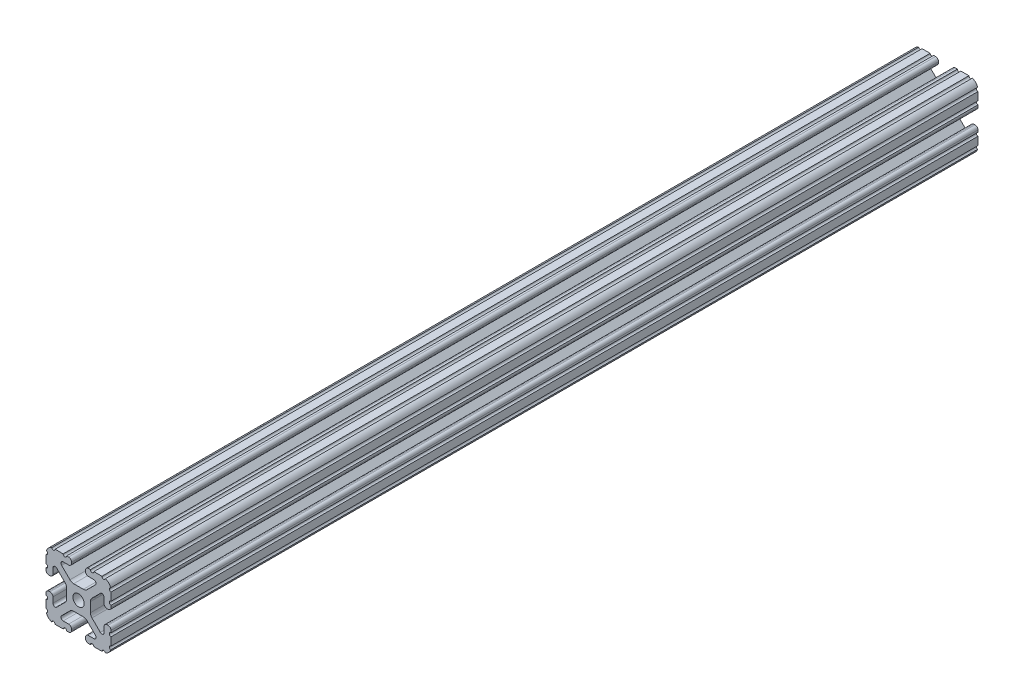
SolidWorks part; units mm, degrees
ref_plane "Front Plane" through (0, 0, 0) normal (0, 0, 1) x (1, 0, 0)
ref_plane "Top Plane" through (0, 0, 0) normal (0, 1, 0) x (1, 0, 0)
ref_plane "Right Plane" through (0, 0, 0) normal (1, 0, 0) x (0, 0, -1)
sketch "Sketch2" plane through (0, 0, 0) normal (0, 0, 1) x (1, 0, 0)
  line L0 (0, 19.05) -> (0, -19.05) construction
  line L1 (-19.05, 0) -> (19.05, 0) construction
  line L2 (4.064, -19.05) -> (19.05, -19.05)
  line L3 (19.05, -19.05) -> (19.05, -4.064)
  line L4 (4.064, -19.05) -> (4.064, -14.986)
  line L5 (4.064, -14.986) -> (12.1123, -14.986)
  line L6 (12.1123, -14.986) -> (4.1113, -6.985)
  line L7 (0, 0) -> (19.05, -19.05) construction
  line L8 (19.05, -4.064) -> (14.986, -4.064)
  line L9 (14.986, -4.064) -> (14.986, -12.1123)
  line L10 (14.986, -12.1123) -> (6.985, -4.1113)
  circle A0 centre (0, 0) radius 3.3274
  arc A1 (8.9963, -14.986) -> (9.909, -12.7826) centre (8.9963, -13.6953) ccw construction
  point P8 (0, -6.985)
  dimension "Center Hole Diameter" = 6.6548
  dimension "Rail Height" = 38.1
  dimension "Rail Width" = 38.1
  dimension "T-Slot Width" = 8.128
  dimension "Slot Inner Width" = 20.574
  dimension "Thickness" = 4.064
  dimension "Slot Depth" = 8.001
  dimension "D1" = 4.064
sketch "Sketch3" plane through (0, 0, 0) normal (1, 0, 0) x (0, 0, -1)
  line L0 (-304.8, -19.05) -> (304.8, -19.05) construction
  line L1 (-279.4, 0) -> (279.4, 0) construction
  dimension "Length" = 609.6
  dimension "D1" = 25.4
sketch "Sketch4" plane through (0, 0, 0) normal (0, 0, 1) x (1, 0, 0)
  line L0 (5.7912, -19.05) -> (14.3002, -19.05)
  line L1 (4.064, -19.05) -> (19.05, -19.05) construction
  line L2 (4.064, -19.05) -> (4.064, -14.986) construction
  line L3 (4.064, -14.986) -> (12.1123, -14.986) construction
  line L4 (4.064, -16.7132) -> (4.064, -17.3228)
  line L5 (5.7912, -14.986) -> (8.9963, -14.986)
  line L6 (0, -6.985) -> (2.833, -6.985)
  line L7 (12.1123, -14.986) -> (4.1113, -6.985) construction
  line L8 (5.0152, -7.8889) -> (9.909, -12.7826)
  line L9 (19.05, -19.05) -> (19.05, -4.064) construction
  line L10 (14.986, -12.1123) -> (6.985, -4.1113) construction
  line L11 (14.986, -4.064) -> (14.986, -12.1123) construction
  line L12 (14.986, -8.9963) -> (14.986, -5.7912)
  line L13 (19.05, -4.064) -> (14.986, -4.064) construction
  line L14 (16.7132, -4.064) -> (17.3228, -4.064)
  line L15 (19.05, -5.7912) -> (19.05, -14.3002)
  line L16 (12.7826, -9.909) -> (7.8889, -5.0152)
  line L17 (6.985, 0) -> (6.985, -2.833)
  line L18 (-19.05, 0) -> (19.05, 0) construction
  line L19 (0, -6.985) -> (0, -3.3274)
  line L20 (0, 19.05) -> (0, -19.05) construction
  line L21 (6.985, 0) -> (3.3274, 0)
  arc A0 (4.064, -17.3228) -> (5.7912, -19.05) centre (5.7912, -17.3228) ccw
  arc A2 (4.064, -16.7132) -> (5.7912, -14.986) centre (5.7912, -16.7132) cw
  arc A3 (8.9963, -14.986) -> (9.909, -12.7826) centre (8.9963, -13.6953) ccw
  arc A4 (2.833, -6.985) -> (5.0152, -7.8889) centre (2.833, -10.0711) cw
  arc A5 (14.3002, -19.05) -> (19.05, -14.3002) centre (14.3002, -14.3002) ccw
  arc A6 (12.7826, -9.909) -> (14.986, -8.9963) centre (13.6953, -8.9963) ccw
  arc A7 (14.986, -5.7912) -> (16.7132, -4.064) centre (16.7132, -5.7912) cw
  arc A8 (17.3228, -4.064) -> (19.05, -5.7912) centre (17.3228, -5.7912) cw
  arc A9 (7.8889, -5.0152) -> (6.985, -2.833) centre (10.0711, -2.833) cw
  circle A10 centre (0, 0) radius 3.3274 construction
  arc A11 (0, -3.3274) -> (3.3274, 0) centre (0, 0) ccw
  dimension "D1" = 4.7498
  dimension "D2" = 3.0861
  dimension "D3" = 1.7272
extrude "Boss-Extrude1" add sketch "Sketch4" along normal mid plane 609.6
sketch "Sketch5" plane through (0, 0, 0) normal (0, 0, 1) x (1, 0, 0)
  line L0 (4.064, -19.05) -> (19.05, -19.05) construction
  line L1 (5.7912, -14.986) -> (8.9963, -14.986) construction
  line L3 (0, 0) -> (19.05, -19.05) construction
  line L4 (8.9963, -14.986) -> (8.9963, -19.05) construction
  line L5 (12.1123, -14.986) -> (4.1113, -6.985) construction
  circle A0 centre (14.7395, -19.05) radius 1.016
  circle A1 centre (7.9803, -19.05) radius 1.016
  circle A2 centre (19.05, -14.7395) radius 1.016
  circle A3 centre (19.05, -7.9803) radius 1.016
  point P10 (7.3938, -14.986)
  point P12 (13.6953, -8.9963)
extrude "Cut-Extrude1" cut sketch "Sketch5" against normal through all both and the other way through all
mirror "Mirror1" about plane through (0, 0, 0) normal (1, 0, 0) of bodies 137 134
mirror "Mirror2" about plane through (0, 0, 0) normal (0, 1, 0) of bodies 135
sketch "Sketch6" plane through (0, 0, -304.8) normal (0, 0, -1) x (-1, 0, 0)
  line L44 (-19.05, -5.7912) -> (-19.05, -6.9643)
  line L45 (-19.05, -8.9963) -> (-19.05, -13.7235)
  line L46 (-13.7235, -19.05) -> (-8.9963, -19.05)
  line L47 (-6.9643, -19.05) -> (-5.7912, -19.05)
  line L48 (-4.064, -17.3228) -> (-4.064, -16.7132)
  line L49 (-5.7912, -14.986) -> (-8.9963, -14.986)
  line L50 (-9.909, -12.7826) -> (-5.0152, -7.8889)
  line L51 (-2.833, -6.985) -> (2.833, -6.985)
  line L52 (5.0152, -7.8889) -> (9.909, -12.7826)
  line L53 (8.9963, -14.986) -> (5.7912, -14.986)
  line L54 (4.064, -16.7132) -> (4.064, -17.3228)
  line L55 (5.7912, -19.05) -> (6.9643, -19.05)
  line L56 (8.9963, -19.05) -> (13.7235, -19.05)
  line L57 (19.05, -13.7235) -> (19.05, -8.9963)
  line L58 (19.05, -6.9643) -> (19.05, -5.7912)
  line L59 (17.3228, -4.064) -> (16.7132, -4.064)
  line L60 (14.986, -5.7912) -> (14.986, -8.9963)
  line L61 (12.7826, -9.909) -> (7.8889, -5.0152)
  line L62 (6.985, -2.833) -> (6.985, 2.833)
  line L63 (7.8889, 5.0152) -> (12.7826, 9.909)
  line L64 (14.986, 8.9963) -> (14.986, 5.7912)
  line L65 (16.7132, 4.064) -> (17.3228, 4.064)
  line L66 (19.05, 5.7912) -> (19.05, 6.9643)
  line L67 (19.05, 8.9963) -> (19.05, 13.7235)
  line L68 (13.7235, 19.05) -> (8.9963, 19.05)
  line L69 (6.9643, 19.05) -> (5.7912, 19.05)
  line L70 (4.064, 17.3228) -> (4.064, 16.7132)
  line L71 (5.7912, 14.986) -> (8.9963, 14.986)
  line L72 (9.909, 12.7826) -> (5.0152, 7.8889)
  line L73 (2.833, 6.985) -> (-2.833, 6.985)
  line L74 (-5.0152, 7.8889) -> (-9.909, 12.7826)
  line L75 (-8.9963, 14.986) -> (-5.7912, 14.986)
  line L76 (-4.064, 16.7132) -> (-4.064, 17.3228)
  line L77 (-5.7912, 19.05) -> (-6.9643, 19.05)
  line L78 (-8.9963, 19.05) -> (-13.7235, 19.05)
  line L79 (-19.05, 13.7235) -> (-19.05, 8.9963)
  line L80 (-19.05, 6.9643) -> (-19.05, 5.7912)
  line L81 (-17.3228, 4.064) -> (-16.7132, 4.064)
  line L82 (-14.986, 5.7912) -> (-14.986, 8.9963)
  line L83 (-12.7826, 9.909) -> (-7.8889, 5.0152)
  line L84 (-6.985, 2.833) -> (-6.985, -2.833)
  line L85 (-7.8889, -5.0152) -> (-12.7826, -9.909)
  line L86 (-14.986, -8.9963) -> (-14.986, -5.7912)
  line L87 (-16.7132, -4.064) -> (-17.3228, -4.064)
  line L88 (-19.05, -5.7912) -> (-19.05, -6.9643)
  line L89 (-19.05, -8.9963) -> (-19.05, -13.7235)
  line L90 (-13.7235, -19.05) -> (-8.9963, -19.05)
  line L91 (-6.9643, -19.05) -> (-5.7912, -19.05)
  line L92 (-4.064, -17.3228) -> (-4.064, -16.7132)
  line L93 (-5.7912, -14.986) -> (-8.9963, -14.986)
  line L94 (-9.909, -12.7826) -> (-5.0152, -7.8889)
  line L95 (-2.833, -6.985) -> (2.833, -6.985)
  line L96 (5.0152, -7.8889) -> (9.909, -12.7826)
  line L97 (8.9963, -14.986) -> (5.7912, -14.986)
  line L98 (4.064, -16.7132) -> (4.064, -17.3228)
  line L99 (5.7912, -19.05) -> (6.9643, -19.05)
  line L100 (8.9963, -19.05) -> (13.7235, -19.05)
  line L101 (19.05, -13.7235) -> (19.05, -8.9963)
  line L102 (19.05, -6.9643) -> (19.05, -5.7912)
  line L103 (17.3228, -4.064) -> (16.7132, -4.064)
  line L104 (14.986, -5.7912) -> (14.986, -8.9963)
  line L105 (12.7826, -9.909) -> (7.8889, -5.0152)
  line L106 (6.985, -2.833) -> (6.985, 2.833)
  line L107 (7.8889, 5.0152) -> (12.7826, 9.909)
  line L108 (14.986, 8.9963) -> (14.986, 5.7912)
  line L109 (16.7132, 4.064) -> (17.3228, 4.064)
  line L110 (19.05, 5.7912) -> (19.05, 6.9643)
  line L111 (19.05, 8.9963) -> (19.05, 13.7235)
  line L112 (13.7235, 19.05) -> (8.9963, 19.05)
  line L113 (6.9643, 19.05) -> (5.7912, 19.05)
  line L114 (4.064, 17.3228) -> (4.064, 16.7132)
  line L115 (5.7912, 14.986) -> (8.9963, 14.986)
  line L116 (9.909, 12.7826) -> (5.0152, 7.8889)
  line L117 (2.833, 6.985) -> (-2.833, 6.985)
  line L118 (-5.0152, 7.8889) -> (-9.909, 12.7826)
  line L119 (-8.9963, 14.986) -> (-5.7912, 14.986)
  line L120 (-4.064, 16.7132) -> (-4.064, 17.3228)
  line L121 (-5.7912, 19.05) -> (-6.9643, 19.05)
  line L122 (-8.9963, 19.05) -> (-13.7235, 19.05)
  line L123 (-19.05, 13.7235) -> (-19.05, 8.9963)
  line L124 (-19.05, 6.9643) -> (-19.05, 5.7912)
  line L125 (-17.3228, 4.064) -> (-16.7132, 4.064)
  line L126 (-14.986, 5.7912) -> (-14.986, 8.9963)
  line L127 (-12.7826, 9.909) -> (-7.8889, 5.0152)
  line L128 (-6.985, 2.833) -> (-6.985, -2.833)
  line L129 (-7.8889, -5.0152) -> (-12.7826, -9.909)
  line L130 (-14.986, -8.9963) -> (-14.986, -5.7912)
  line L131 (-16.7132, -4.064) -> (-17.3228, -4.064)
  circle A1 centre (0, 0) radius 3.3274
  circle A2 centre (0, 0) radius 3.3274
  arc A54 (-19.05, -8.9963) -> (-19.05, -6.9643) centre (-19.05, -7.9803) ccw
  arc A55 (-18.8293, -15.7312) -> (-19.05, -13.7235) centre (-19.05, -14.7395) ccw
  arc A56 (-18.8293, -15.7312) -> (-15.7312, -18.8293) centre (-14.3002, -14.3002) ccw
  arc A57 (-13.7235, -19.05) -> (-15.7312, -18.8293) centre (-14.7395, -19.05) ccw
  arc A58 (-6.9643, -19.05) -> (-8.9963, -19.05) centre (-7.9803, -19.05) ccw
  arc A59 (-5.7912, -19.05) -> (-4.064, -17.3228) centre (-5.7912, -17.3228) ccw
  arc A60 (-4.064, -16.7132) -> (-5.7912, -14.986) centre (-5.7912, -16.7132) ccw
  arc A61 (-9.909, -12.7826) -> (-8.9963, -14.986) centre (-8.9963, -13.6953) ccw
  arc A62 (-2.833, -6.985) -> (-5.0152, -7.8889) centre (-2.833, -10.0711) ccw
  arc A63 (5.0152, -7.8889) -> (2.833, -6.985) centre (2.833, -10.0711) ccw
  arc A64 (8.9963, -14.986) -> (9.909, -12.7826) centre (8.9963, -13.6953) ccw
  arc A65 (5.7912, -14.986) -> (4.064, -16.7132) centre (5.7912, -16.7132) ccw
  arc A66 (4.064, -17.3228) -> (5.7912, -19.05) centre (5.7912, -17.3228) ccw
  arc A67 (8.9963, -19.05) -> (6.9643, -19.05) centre (7.9803, -19.05) ccw
  arc A68 (15.7312, -18.8293) -> (13.7235, -19.05) centre (14.7395, -19.05) ccw
  arc A69 (15.7312, -18.8293) -> (18.8293, -15.7312) centre (14.3002, -14.3002) ccw
  arc A70 (19.05, -13.7235) -> (18.8293, -15.7312) centre (19.05, -14.7395) ccw
  arc A71 (19.05, -6.9643) -> (19.05, -8.9963) centre (19.05, -7.9803) ccw
  arc A72 (19.05, -5.7912) -> (17.3228, -4.064) centre (17.3228, -5.7912) ccw
  arc A73 (16.7132, -4.064) -> (14.986, -5.7912) centre (16.7132, -5.7912) ccw
  arc A74 (12.7826, -9.909) -> (14.986, -8.9963) centre (13.6953, -8.9963) ccw
  arc A75 (6.985, -2.833) -> (7.8889, -5.0152) centre (10.0711, -2.833) ccw
  arc A76 (7.8889, 5.0152) -> (6.985, 2.833) centre (10.0711, 2.833) ccw
  arc A77 (14.986, 8.9963) -> (12.7826, 9.909) centre (13.6953, 8.9963) ccw
  arc A78 (14.986, 5.7912) -> (16.7132, 4.064) centre (16.7132, 5.7912) ccw
  arc A79 (17.3228, 4.064) -> (19.05, 5.7912) centre (17.3228, 5.7912) ccw
  arc A80 (19.05, 8.9963) -> (19.05, 6.9643) centre (19.05, 7.9803) ccw
  arc A81 (18.8293, 15.7312) -> (19.05, 13.7235) centre (19.05, 14.7395) ccw
  arc A82 (18.8293, 15.7312) -> (15.7312, 18.8293) centre (14.3002, 14.3002) ccw
  arc A83 (13.7235, 19.05) -> (15.7312, 18.8293) centre (14.7395, 19.05) ccw
  arc A84 (6.9643, 19.05) -> (8.9963, 19.05) centre (7.9803, 19.05) ccw
  arc A85 (5.7912, 19.05) -> (4.064, 17.3228) centre (5.7912, 17.3228) ccw
  arc A86 (4.064, 16.7132) -> (5.7912, 14.986) centre (5.7912, 16.7132) ccw
  arc A87 (9.909, 12.7826) -> (8.9963, 14.986) centre (8.9963, 13.6953) ccw
  arc A88 (2.833, 6.985) -> (5.0152, 7.8889) centre (2.833, 10.0711) ccw
  arc A89 (-5.0152, 7.8889) -> (-2.833, 6.985) centre (-2.833, 10.0711) ccw
  arc A90 (-8.9963, 14.986) -> (-9.909, 12.7826) centre (-8.9963, 13.6953) ccw
  arc A91 (-5.7912, 14.986) -> (-4.064, 16.7132) centre (-5.7912, 16.7132) ccw
  arc A92 (-4.064, 17.3228) -> (-5.7912, 19.05) centre (-5.7912, 17.3228) ccw
  arc A93 (-8.9963, 19.05) -> (-6.9643, 19.05) centre (-7.9803, 19.05) ccw
  arc A94 (-15.7312, 18.8293) -> (-13.7235, 19.05) centre (-14.7395, 19.05) ccw
  arc A95 (-15.7312, 18.8293) -> (-18.8293, 15.7312) centre (-14.3002, 14.3002) ccw
  arc A96 (-19.05, 13.7235) -> (-18.8293, 15.7312) centre (-19.05, 14.7395) ccw
  arc A97 (-19.05, 6.9643) -> (-19.05, 8.9963) centre (-19.05, 7.9803) ccw
  arc A98 (-19.05, 5.7912) -> (-17.3228, 4.064) centre (-17.3228, 5.7912) ccw
  arc A99 (-16.7132, 4.064) -> (-14.986, 5.7912) centre (-16.7132, 5.7912) ccw
  arc A100 (-12.7826, 9.909) -> (-14.986, 8.9963) centre (-13.6953, 8.9963) ccw
  arc A101 (-6.985, 2.833) -> (-7.8889, 5.0152) centre (-10.0711, 2.833) ccw
  arc A102 (-7.8889, -5.0152) -> (-6.985, -2.833) centre (-10.0711, -2.833) ccw
  arc A103 (-14.986, -8.9963) -> (-12.7826, -9.909) centre (-13.6953, -8.9963) ccw
  arc A104 (-14.986, -5.7912) -> (-16.7132, -4.064) centre (-16.7132, -5.7912) ccw
  arc A105 (-17.3228, -4.064) -> (-19.05, -5.7912) centre (-17.3228, -5.7912) ccw
  arc A106 (-19.05, -8.9963) -> (-19.05, -6.9643) centre (-19.05, -7.9803) ccw
  arc A107 (-18.8293, -15.7312) -> (-19.05, -13.7235) centre (-19.05, -14.7395) ccw
  arc A108 (-18.8293, -15.7312) -> (-15.7312, -18.8293) centre (-14.3002, -14.3002) ccw
  arc A109 (-13.7235, -19.05) -> (-15.7312, -18.8293) centre (-14.7395, -19.05) ccw
  arc A110 (-6.9643, -19.05) -> (-8.9963, -19.05) centre (-7.9803, -19.05) ccw
  arc A111 (-5.7912, -19.05) -> (-4.064, -17.3228) centre (-5.7912, -17.3228) ccw
  arc A112 (-4.064, -16.7132) -> (-5.7912, -14.986) centre (-5.7912, -16.7132) ccw
  arc A113 (-9.909, -12.7826) -> (-8.9963, -14.986) centre (-8.9963, -13.6953) ccw
  arc A114 (-2.833, -6.985) -> (-5.0152, -7.8889) centre (-2.833, -10.0711) ccw
  arc A115 (5.0152, -7.8889) -> (2.833, -6.985) centre (2.833, -10.0711) ccw
  arc A116 (8.9963, -14.986) -> (9.909, -12.7826) centre (8.9963, -13.6953) ccw
  arc A117 (5.7912, -14.986) -> (4.064, -16.7132) centre (5.7912, -16.7132) ccw
  arc A118 (4.064, -17.3228) -> (5.7912, -19.05) centre (5.7912, -17.3228) ccw
  arc A119 (8.9963, -19.05) -> (6.9643, -19.05) centre (7.9803, -19.05) ccw
  arc A120 (15.7312, -18.8293) -> (13.7235, -19.05) centre (14.7395, -19.05) ccw
  arc A121 (15.7312, -18.8293) -> (18.8293, -15.7312) centre (14.3002, -14.3002) ccw
  arc A122 (19.05, -13.7235) -> (18.8293, -15.7312) centre (19.05, -14.7395) ccw
  arc A123 (19.05, -6.9643) -> (19.05, -8.9963) centre (19.05, -7.9803) ccw
  arc A124 (19.05, -5.7912) -> (17.3228, -4.064) centre (17.3228, -5.7912) ccw
  arc A125 (16.7132, -4.064) -> (14.986, -5.7912) centre (16.7132, -5.7912) ccw
  arc A126 (12.7826, -9.909) -> (14.986, -8.9963) centre (13.6953, -8.9963) ccw
  arc A127 (6.985, -2.833) -> (7.8889, -5.0152) centre (10.0711, -2.833) ccw
  arc A128 (7.8889, 5.0152) -> (6.985, 2.833) centre (10.0711, 2.833) ccw
  arc A129 (14.986, 8.9963) -> (12.7826, 9.909) centre (13.6953, 8.9963) ccw
  arc A130 (14.986, 5.7912) -> (16.7132, 4.064) centre (16.7132, 5.7912) ccw
  arc A131 (17.3228, 4.064) -> (19.05, 5.7912) centre (17.3228, 5.7912) ccw
  arc A132 (19.05, 8.9963) -> (19.05, 6.9643) centre (19.05, 7.9803) ccw
  arc A133 (18.8293, 15.7312) -> (19.05, 13.7235) centre (19.05, 14.7395) ccw
  arc A134 (18.8293, 15.7312) -> (15.7312, 18.8293) centre (14.3002, 14.3002) ccw
  arc A135 (13.7235, 19.05) -> (15.7312, 18.8293) centre (14.7395, 19.05) ccw
  arc A136 (6.9643, 19.05) -> (8.9963, 19.05) centre (7.9803, 19.05) ccw
  arc A137 (5.7912, 19.05) -> (4.064, 17.3228) centre (5.7912, 17.3228) ccw
  arc A138 (4.064, 16.7132) -> (5.7912, 14.986) centre (5.7912, 16.7132) ccw
  arc A139 (9.909, 12.7826) -> (8.9963, 14.986) centre (8.9963, 13.6953) ccw
  arc A140 (2.833, 6.985) -> (5.0152, 7.8889) centre (2.833, 10.0711) ccw
  arc A141 (-5.0152, 7.8889) -> (-2.833, 6.985) centre (-2.833, 10.0711) ccw
  arc A142 (-8.9963, 14.986) -> (-9.909, 12.7826) centre (-8.9963, 13.6953) ccw
  arc A143 (-5.7912, 14.986) -> (-4.064, 16.7132) centre (-5.7912, 16.7132) ccw
  arc A144 (-4.064, 17.3228) -> (-5.7912, 19.05) centre (-5.7912, 17.3228) ccw
  arc A145 (-8.9963, 19.05) -> (-6.9643, 19.05) centre (-7.9803, 19.05) ccw
  arc A146 (-15.7312, 18.8293) -> (-13.7235, 19.05) centre (-14.7395, 19.05) ccw
  arc A147 (-15.7312, 18.8293) -> (-18.8293, 15.7312) centre (-14.3002, 14.3002) ccw
  arc A148 (-19.05, 13.7235) -> (-18.8293, 15.7312) centre (-19.05, 14.7395) ccw
  arc A149 (-19.05, 6.9643) -> (-19.05, 8.9963) centre (-19.05, 7.9803) ccw
  arc A150 (-19.05, 5.7912) -> (-17.3228, 4.064) centre (-17.3228, 5.7912) ccw
  arc A151 (-16.7132, 4.064) -> (-14.986, 5.7912) centre (-16.7132, 5.7912) ccw
  arc A152 (-12.7826, 9.909) -> (-14.986, 8.9963) centre (-13.6953, 8.9963) ccw
  arc A153 (-6.985, 2.833) -> (-7.8889, 5.0152) centre (-10.0711, 2.833) ccw
  arc A154 (-7.8889, -5.0152) -> (-6.985, -2.833) centre (-10.0711, -2.833) ccw
  arc A155 (-14.986, -8.9963) -> (-12.7826, -9.909) centre (-13.6953, -8.9963) ccw
  arc A156 (-14.986, -5.7912) -> (-16.7132, -4.064) centre (-16.7132, -5.7912) ccw
  arc A157 (-17.3228, -4.064) -> (-19.05, -5.7912) centre (-17.3228, -5.7912) ccw
  dimension "D1" = 0
  dimension "D2" = 0
extrude "Cut-Extrude2" cut sketch "Sketch6" against normal blind 101.6
equation "\"D1@Boss-Extrude1\"=\"Length@Sketch3\""
equation "\"D1@Sketch2\"=\"Thickness@Sketch2\""
equation "\"D2@Sketch4\"=\"Slot Inner Width@Sketch2\"*0.15"
equation "\"D1@Sketch4\"=\"D3@Sketch4\"*2.75"
equation "\"D3@Sketch4\"=\"Thickness@Sketch2\"*0.425"
equation "\"D1@Sketch5\"=\"Thickness@Sketch2\"*0.5"
